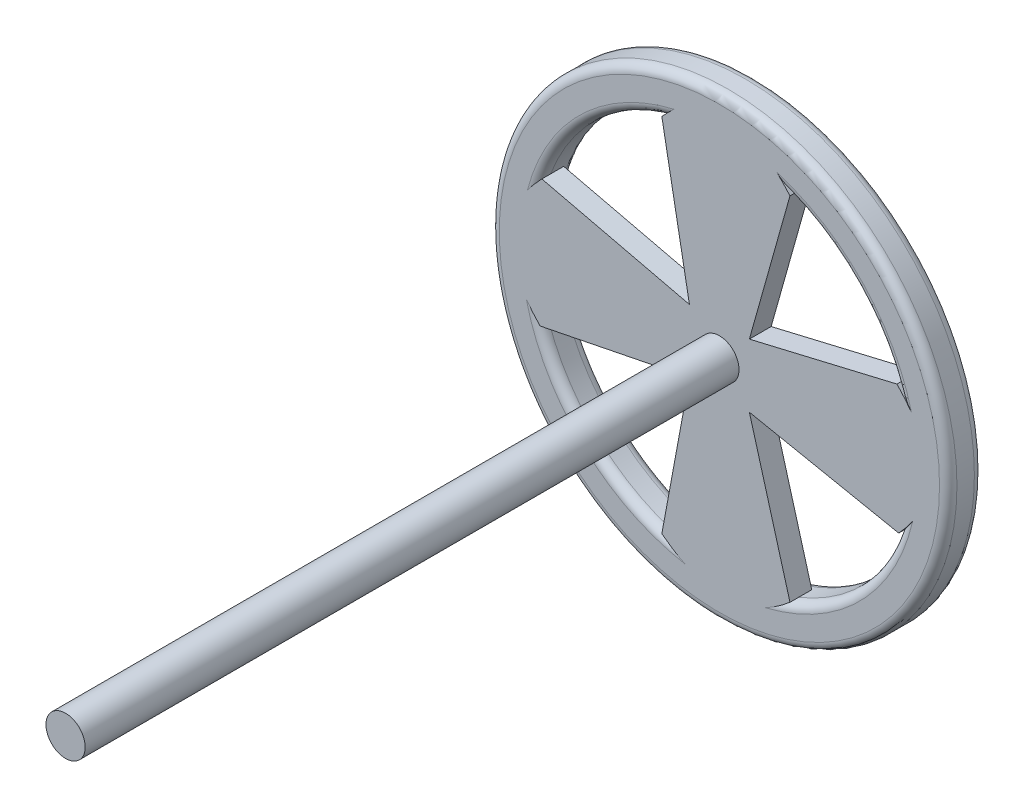
SolidWorks part; units mm, degrees
ref_plane "Front Plane" through (0, 0, 0) normal (0, 0, 1) x (1, 0, 0)
ref_plane "Top Plane" through (0, 0, 0) normal (0, 1, 0) x (1, 0, 0)
ref_plane "Right Plane" through (0, 0, 0) normal (1, 0, 0) x (0, 0, -1)
sketch "Sketch1" plane through (0, 0, 0) normal (0, 0, 1) x (1, 0, 0)
  circle A0 centre (0, 0) radius 133.35
  circle A1 centre (0, 0) radius 110.49
  dimension "D1" = 266.7
  dimension "D2" = 220.98
extrude "Boss-Extrude1" add sketch "Sketch1" along normal blind 20.32
fillet "Fillet1" radius 5.08 1 edges at (133.35, 0, 20.32)
fillet "Fillet4" radius 5.08 1 edges at (133.35, 0, 0)
fillet "Fillet5" radius 5.08 1 edges at (110.49, 0, 20.32)
fillet "Fillet6" radius 5.08 1 edges at (110.49, 0, 0)
sketch "Sketch2" plane through (0, 0, 20.32) normal (0, 0, 1) x (1, 0, 0)
  line L0 (103.4658, 38.767) -> (17.4654, 18.4424) construction
  line L1 (41.1209, 102.553) -> (17.4654, 18.4424) construction
  line L2 (-103.4537, 38.7991) -> (-17.4654, 18.4424) construction
  line L3 (-33.5456, 105.2746) -> (-17.4654, 18.4424) construction
  line L4 (104.4809, -35.9413) -> (17.4654, -18.4424) construction
  line L5 (41.1209, -102.553) -> (17.4654, -18.4424) construction
  line L6 (-33.5456, -105.2746) -> (-17.4654, -18.4424) construction
  line L7 (-104.492, -35.909) -> (-17.4654, -18.4424) construction
  line L8 (103.4658, 38.767) -> (17.4654, 18.4424)
  line L9 (41.1209, 102.553) -> (17.4654, 18.4424)
  line L10 (-33.5456, 105.2746) -> (-17.4654, 18.4424)
  line L11 (-103.4537, 38.7991) -> (-17.4654, 18.4424)
  line L12 (-104.492, -35.909) -> (-17.4654, -18.4424)
  line L13 (-33.5456, -105.2746) -> (-17.4654, -18.4424)
  line L14 (41.1209, -102.553) -> (17.4654, -18.4424)
  line L15 (104.4809, -35.9413) -> (17.4654, -18.4424)
  circle A0 centre (0, 0) radius 110.49 construction
  circle A1 centre (0, 0) radius 25.4
  spline S0 degree 2 poles (104.4809, -35.9413) (139.512, 1.2852) (103.4658, 38.767) knots 0 0 0 1 1 1
  spline S1 degree 2 poles (-33.5456, -105.2746) (3.664, -134.23) (41.1209, -102.553) knots 0 0 0 1 1 1
  spline S2 degree 2 poles (-104.492, -35.909) (-140.4141, 1.2987) (-103.4537, 38.7991) knots 0 0 0 1 1 1
  spline S3 degree 2 poles (-33.5456, 105.2746) (3.0882, 146.6816) (41.1209, 102.553) knots 0 0 0 1 1 1
  dimension "D1" = 50.8
extrude "Boss-Extrude2" add sketch "Sketch2" against normal blind 12.7 separate body
sketch "Sketch3" plane through (0, 0, 20.32) normal (0, 0, 1) x (1, 0, 0)
  circle A0 centre (0, 0) radius 11.43
  dimension "D1" = 22.86
extrude "Boss-Extrude3" add sketch "Sketch3" along normal blind 381
